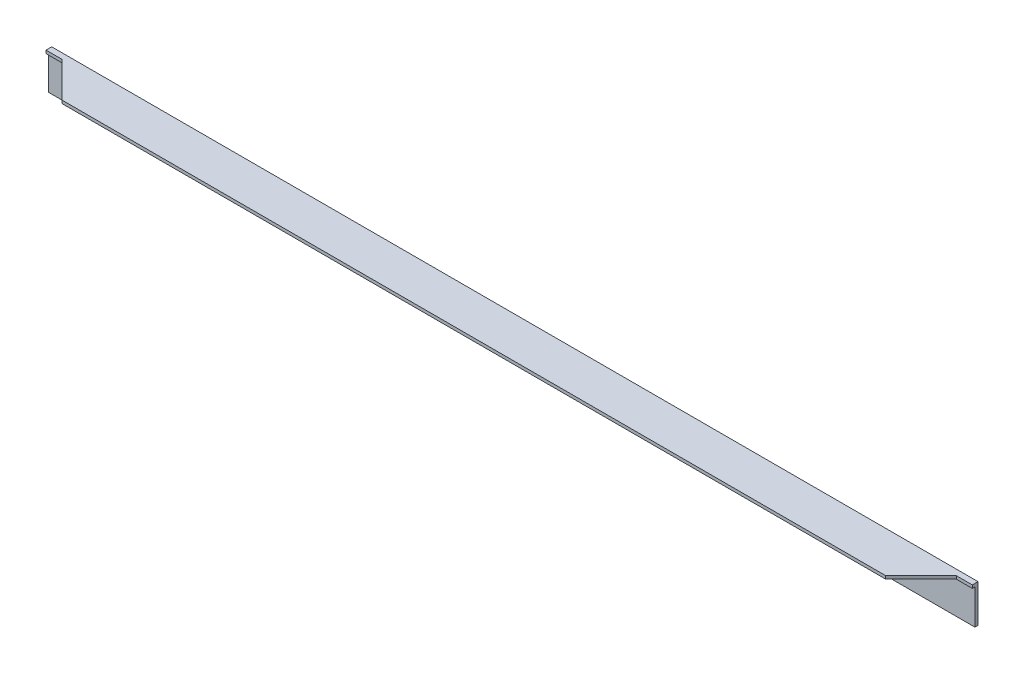
SolidWorks part; units mm, degrees
ref_plane "前视" through (0, 0, 0) normal (0, 0, 1) x (1, 0, 0)
ref_plane "上视" through (0, 0, 0) normal (0, 1, 0) x (1, 0, 0)
ref_plane "右视" through (0, 0, 0) normal (1, 0, 0) x (0, 0, -1)
sketch "草图1" plane through (0, 0, 0) normal (0, 0, 1) x (1, 0, 0)
  line L0 (0, 0) -> (0, 1201.1794) construction
  line L1 (-1220, 0) -> (1220, 0)
  line L2 (-1220, 0) -> (-1220, 100)
  line L3 (-1220, 100) -> (1220, 100)
  line L4 (1220, 0) -> (1220, 100)
  line L5 (1220, 40) -> (160, 40) construction
  line L6 (1220, 40) -> (80, 40) construction
  line L7 (0, 0) -> (1220, 0) construction
  line L8 (1170, 0) -> (1170, 100) construction
  line L9 (160, 100) -> (160, 40) construction
  line L10 (1090, 0) -> (1090, 100) construction
  line L11 (1414, 100) -> (1414, 0) construction
  line L12 (80, 40) -> (-1220, 40) construction
  line L13 (-1414, 582.7434) -> (-1414, -1649.9569) construction
  dimension "D4" = 50
  dimension "D5" = 80
  dimension "D8" = 80
  dimension "D1" = 2440
  dimension "D2" = 100
  dimension "D3" = 40
extrude "基体-拉伸" add sketch "草图1" along normal blind 8
sketch "草图2" plane through (0, 0, 8) normal (0, 0, 1) x (1, 0, 0)
  line L0 (1220, 0) -> (1220, 100) construction
  line L1 (-1220, 100) -> (1220, 100)
  line L2 (-1220, 100) -> (-1220, 92)
  line L3 (-1220, 92) -> (1220, 92)
  line L4 (1220, 100) -> (1220, 92)
  dimension "D1" = 8
extrude "凸台-拉伸1" add sketch "草图2" along normal blind 100
sketch "草图3" plane through (0, 100, 0) normal (0, 1, 0) x (-1, 0, 0)
  line L2 (-1220, 108) -> (-1220, 0) construction
  line L3 (-1220, 0) -> (1220, 0) construction
  line L4 (-1220, 108) -> (1220, 108) construction
  line L5 (-1085, 108) -> (-1178, 15)
  line L6 (-1085, 108) -> (-1220, 108)
  line L7 (-1220, 108) -> (-1220, 15)
  line L8 (-1220, 15) -> (-1178, 15)
  line L9 (0, 868.9044) -> (0, -812.8803) construction
  line L10 (1220, 108) -> (1220, 0) construction
  line L11 (1220, 15) -> (1178, 15)
  line L12 (1220, 108) -> (1220, 15)
  line L13 (1085, 108) -> (1220, 108)
  line L14 (1085, 108) -> (1178, 15)
  point P0 (-1220, 15)
  point P5 (-1085, 108)
  dimension "D1" = 15
  dimension "D2" = 135
  dimension "D3" = 45
extrude "切除-拉伸1" cut sketch "草图3" against normal through all
